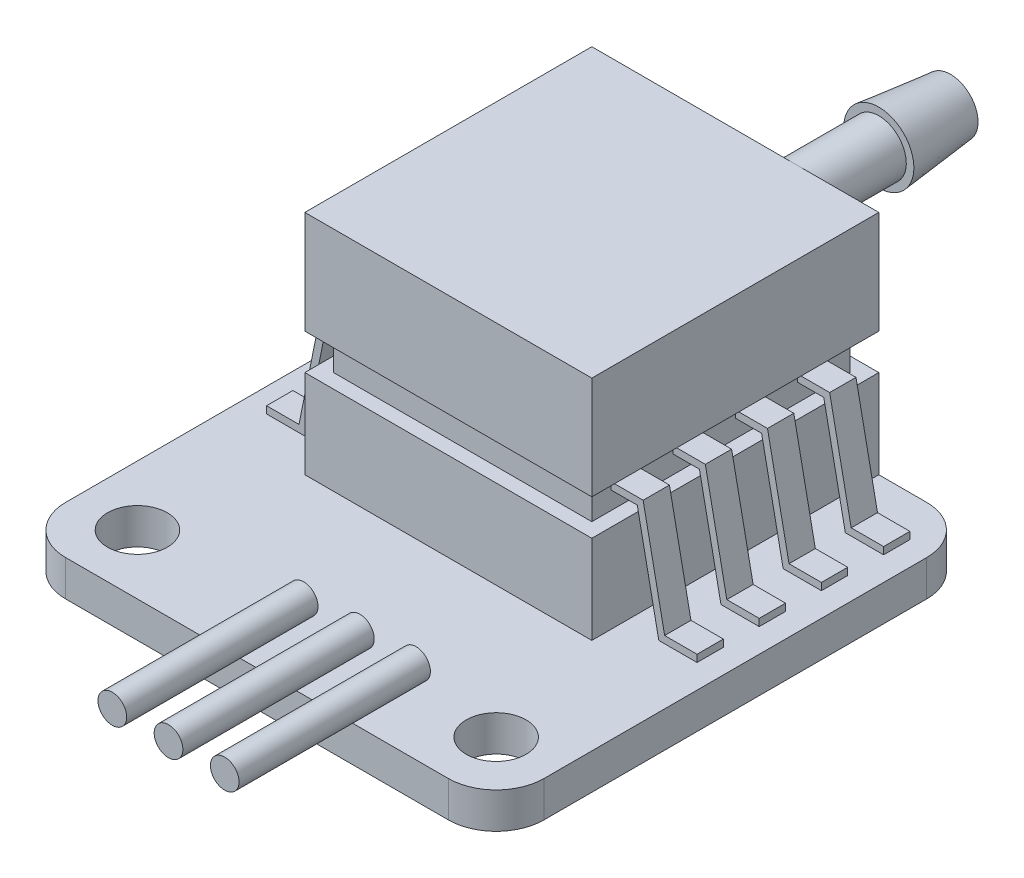
SolidWorks part; units mm, degrees
ref_plane "Спереди" through (0, 0, 0) normal (0, 0, 1) x (1, 0, 0)
ref_plane "Сверху" through (0, 0, 0) normal (0, 1, 0) x (1, 0, 0)
ref_plane "Справа" through (0, 0, 0) normal (1, 0, 0) x (0, 0, -1)
sketch "Эскиз1" plane through (0, 0, 0) normal (0, 1, 0) x (1, 0, 0)
  line L0 (2.5, 2.5) -> (17.5, 2.5) construction
  line L1 (2, 0) -> (18, 0)
  line L2 (0, 2) -> (0, 18)
  line L3 (2, 20) -> (18, 20)
  line L4 (20, 2) -> (20, 18)
  line L5 (10, 2.5) -> (10, 0) construction
  circle A0 centre (2.5, 2.5) radius 1.25
  circle A1 centre (17.5, 2.5) radius 1.25
  arc A2 (20, 2) -> (18, 0) centre (18, 2) cw
  arc A3 (2, 0) -> (0, 2) centre (2, 2) cw
  arc A4 (0, 18) -> (2, 20) centre (2, 18) cw
  arc A5 (18, 20) -> (20, 18) centre (18, 18) cw
  point P13 (0, 0)
  dimension "D3" = 2
  dimension "D5" = 2.5
  dimension "D1" = 20
  dimension "D2" = 20
  dimension "D4" = 15
  dimension "D6" = 2.5
extrude "Бобышка-Вытянуть1" add sketch "Эскиз1" along normal blind 1.5
sketch "Эскиз2" plane through (0, 1.5, 0) normal (0, 1, 0) x (1, 0, 0)
  line L0 (18, 20) -> (2, 20) construction
  line L1 (4, 20) -> (16, 20)
  line L2 (4, 20) -> (4, 8)
  line L3 (4, 8) -> (16, 8)
  line L4 (16, 20) -> (16, 8)
  line L5 (10, 20) -> (10, 8) construction
  point P8 (0, 0)
  dimension "D1" = 12
  dimension "D2" = 12
extrude "Бобышка-Вытянуть2" add sketch "Эскиз2" along normal blind 9.5
sketch "Эскиз3" plane through (0, 1.5, 0) normal (0, 1, 0) x (1, 0, 0)
  line L4 (10, 8) -> (10, 20) construction
  line L5 (15.4, 19.4) -> (4.6, 19.4)
  line L6 (15.4, 19.4) -> (15.4, 8.6)
  line L7 (15.4, 8.6) -> (4.6, 8.6)
  line L8 (4.6, 19.4) -> (4.6, 8.6)
  line L9 (4, 8) -> (16, 8) construction
  line L10 (16, 20) -> (4, 20) construction
  line L11 (4.6, 19.4) -> (15.4, 8.6) construction
  point P10 (10, 14)
  point P11 (10, 14)
  dimension "D1" = 10.8
  dimension "D2" = 10.8
extrude "Вырез-Вытянуть1" cut sketch "Эскиз3" along normal blind 1.5 from offset 3.7 flip side to cut
sketch "Эскиз4" plane through (0, 0, -20) normal (0, 0, -1) x (-1, 0, 0)
  line L0 (-16, 11) -> (-16, 6.7) construction
  line L1 (-16, 11) -> (-4, 11) construction
  line L2 (-4, 1.5) -> (-2, 1.5) construction
  line L3 (-4, 5.2) -> (-4, 1.5) construction
  circle A0 centre (-12.5, 9.85) radius 1.15
  circle A1 centre (-7.5, 2.65) radius 1.15
  circle A2 centre (-12.5, 9.85) radius 0.6
  circle A3 centre (-7.5, 2.65) radius 0.6
  dimension "D2" = 2.3
  dimension "D4" = 1.2
  dimension "D1" = 3.5
  dimension "D3" = 3.5
extrude "Бобышка-Вытянуть3" add sketch "Эскиз4" along normal blind 6.5
sketch "Эскиз5" plane through (0, 0, -26.5) normal (0, 0, -1) x (-1, 0, 0)
  circle A1 centre (-7.5, 2.65) radius 1.15 construction
  circle A2 centre (-7.5, 2.65) radius 1.15
  circle A3 centre (-12.5, 9.85) radius 1.15 construction
  circle A4 centre (-12.5, 9.85) radius 1.15
  circle A5 centre (-12.5, 9.85) radius 0.6 construction
  circle A6 centre (-12.5, 9.85) radius 0.6
  circle A7 centre (-7.5, 2.65) radius 0.6 construction
  circle A8 centre (-7.5, 2.65) radius 0.6
extrude "Бобышка-Вытянуть4" add sketch "Эскиз5" against normal blind 3 draft 6 draft outward yes
sketch "Эскиз6" plane through (0, 0, -20) normal (0, 0, -1) x (-1, 0, 0)
  line L0 (-17.4, 1.5) -> (-19, 1.5)
  line L1 (-18, 1.5) -> (-16, 1.5) construction
  line L2 (-17.4, 1.5) -> (-16.5, 5.95)
  line L3 (-16.5, 5.95) -> (-15.4, 5.95)
  line L4 (-10, 5.2) -> (-10, 1.5) construction
  line L5 (-16, 5.2) -> (-4, 5.2) construction
  line L6 (-3.5, 5.95) -> (-4.6, 5.95)
  line L7 (-2.6, 1.5) -> (-3.5, 5.95)
  line L8 (-2.6, 1.5) -> (-1, 1.5)
  line L9 (-15.4, 6.7) -> (-15.4, 5.2) construction
  point P14 (-15.1258, 6.0727)
  dimension "D1" = 13
  dimension "D2" = 14.8
  dimension "D3" = 18
extrude "Вытянуть-Тонкостенный1" add sketch "Эскиз6" against normal blind 1.1 from offset 1.7 thin offset against normal yes
pattern_linear "Линейный массив1" count 4 spacing 2.6 along (0, 0, 1) of "Вытянуть-Тонкостенный1"
sketch "Эскиз7" plane through (0, 0, 0) normal (0, 0, 1) x (1, 0, 0)
  line L0 (8.95, 2) -> (13.65, 2) construction
  line L1 (2, 1.5) -> (18, 1.5) construction
  line L2 (20, 1.5) -> (20, 0) construction
  circle A0 centre (8.95, 2) radius 0.6
  circle A1 centre (11.3, 2) radius 0.6
  circle A2 centre (13.65, 2) radius 0.6
  point P6 (12.3584, 1.7539)
  dimension "D1" = 1.2
  dimension "D2" = 0.5
  dimension "D3" = 4.7
  dimension "D4" = 8.7
extrude "Бобышка-Вытянуть5" add sketch "Эскиз7" along normal blind 5 and the other way blind 3
